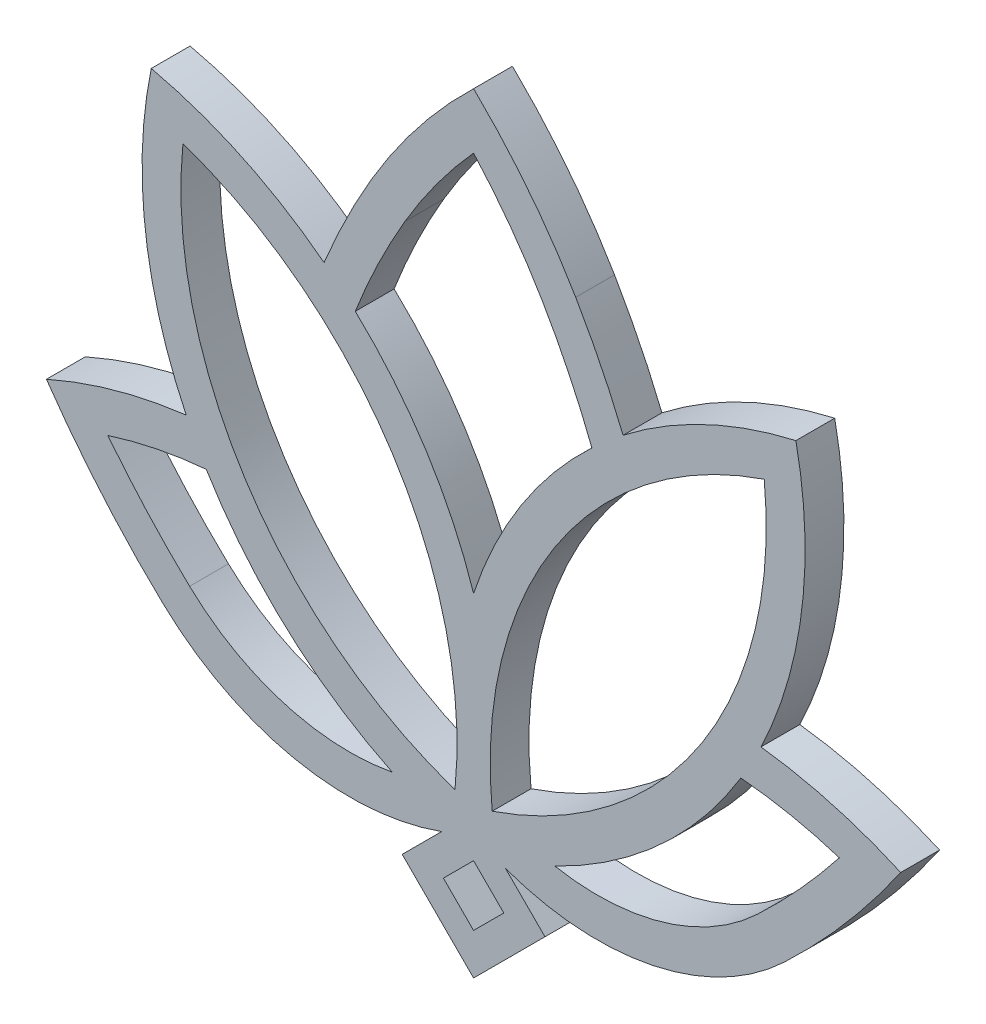
SolidWorks part; units mm, degrees
ref_plane "Front Plane" through (0, 0, 0) normal (0, 0, 1) x (1, 0, 0)
ref_plane "Top Plane" through (0, 0, 0) normal (0, 1, 0) x (1, 0, 0)
ref_plane "Right Plane" through (0, 0, 0) normal (1, 0, 0) x (0, 0, -1)
sketch "Sketch1" plane through (0, 0, 0) normal (0, 0, 1) x (1, 0, 0)
  line L0 (135.2147, 495.9847) -> (817.8814, 495.9847) construction
  line L1 (0, 30.9437) -> (0, -6.9458) construction
  line L2 (0, -55) -> (0, 55) construction
  line L3 (0, 0) -> (1.8385, 1.8385)
  line L4 (1.8385, 1.8385) -> (0.8237, 2.8533)
  line L5 (7.4845, 14.8656) -> (0.479, 3.9593) construction
  line L6 (-5, 0) -> (5, 0) construction
  line L7 (55, 0) -> (-55, 0) construction
  line L9 (0, 1.0607) -> (0.7778, 1.8385)
  line L10 (0.7778, 1.8385) -> (0, 2.6163)
  line L11 (-7.4845, 14.8656) -> (-0.479, 3.9593) construction
  line L12 (-0.7778, 1.8385) -> (0, 2.6163)
  line L13 (0, 1.0607) -> (-0.7778, 1.8385)
  line L14 (-1.8385, 1.8385) -> (-0.8237, 2.8533)
  line L15 (0, 0) -> (-1.8385, 1.8385)
  arc A0 (11, 7.8533) -> (7.4, 8.8533) centre (5.8871, -3.573) ccw
  arc A1 (0.8237, 2.8533) -> (8, 4.3533) centre (3.1917, 9.4406) ccw
  arc A2 (11, 7.8533) -> (8, 4.3533) centre (-7.1117, 20.3419) cw
  arc A3 (7.4, 8.8533) -> (8.3, 16.1351) centre (-2.8806, 13.8204) ccw
  arc A4 (8.3, 16.1351) -> (3.85, 14.0292) centre (10.8441, 5.0044) ccw
  arc A5 (3.85, 14.0292) -> (2.63, 16.4955) centre (-14.0152, 6.7268) ccw
  arc A6 (2.63, 16.4955) -> (0, 19.8333) centre (-10.8241, 8.5995) ccw
  arc A7 (1.7676, 15.9893) -> (3.0463, 13.3446) centre (-14.0152, 6.7268) cw
  arc A8 (1.7676, 15.9893) -> (0, 18.3974) centre (-10.8241, 8.5995) ccw
  arc A9 (3.0463, 13.3446) -> (0, 8.5778) centre (10.8441, 5.0044) ccw
  arc A10 (7.4845, 14.8656) -> (0.479, 3.9593) centre (10.8441, 5.0044) ccw
  arc A11 (7.4845, 14.8656) -> (0.479, 3.9593) centre (-2.8806, 13.8204) cw
  arc A12 (2.0916, 3.5423) -> (7.3131, 5.08) centre (3.1917, 9.4406) ccw
  arc A13 (9.4187, 7.3903) -> (7.3131, 5.08) centre (-7.1117, 20.3419) cw
  arc A14 (2.0916, 3.5423) -> (6.8833, 7.9019) centre (-2.8806, 13.8204) ccw
  arc A15 (6.8833, 7.9019) -> (9.4187, 7.3903) centre (5.8871, -3.573) cw
  arc A16 (-6.8833, 7.9019) -> (-9.4187, 7.3903) centre (-5.8871, -3.573) ccw
  arc A17 (-2.0916, 3.5423) -> (-6.8833, 7.9019) centre (2.8806, 13.8204) cw
  arc A18 (-9.4187, 7.3903) -> (-7.3131, 5.08) centre (7.1117, 20.3419) ccw
  arc A19 (-2.0916, 3.5423) -> (-7.3131, 5.08) centre (-3.1917, 9.4406) cw
  arc A20 (-7.4845, 14.8656) -> (-0.479, 3.9593) centre (2.8806, 13.8204) ccw
  arc A21 (-7.4845, 14.8656) -> (-0.479, 3.9593) centre (-10.8441, 5.0044) cw
  arc A22 (-3.0463, 13.3446) -> (0, 8.5778) centre (-10.8441, 5.0044) cw
  arc A23 (-1.7676, 15.9893) -> (0, 18.3974) centre (10.8241, 8.5995) cw
  arc A24 (-1.7676, 15.9893) -> (-3.0463, 13.3446) centre (14.0152, 6.7268) ccw
  arc A25 (-2.63, 16.4955) -> (0, 19.8333) centre (10.8241, 8.5995) cw
  arc A26 (-3.85, 14.0292) -> (-2.63, 16.4955) centre (14.0152, 6.7268) cw
  arc A27 (-8.3, 16.1351) -> (-3.85, 14.0292) centre (-10.8441, 5.0044) cw
  arc A28 (-7.4, 8.8533) -> (-8.3, 16.1351) centre (2.8806, 13.8204) cw
  arc A29 (-11, 7.8533) -> (-8, 4.3533) centre (7.1117, 20.3419) ccw
  arc A30 (-0.8237, 2.8533) -> (-8, 4.3533) centre (-3.1917, 9.4406) cw
  arc A31 (-11, 7.8533) -> (-7.4, 8.8533) centre (-5.8871, -3.573) cw
  point P40 (0, 0)
  point P75 (0, 0)
  point P76 (0, 0)
  point P77 (0, 0)
  dimension "D1" = 0
  dimension "D2" = 1
  dimension "D3" = 1
  dimension "D4" = 2.6
  dimension "D5" = 5
  dimension "D6" = 0
  dimension "D7" = 1
  dimension "D8" = 1
  dimension "D9" = 45
  dimension "D10" = 12.518
  dimension "D11" = 7
  dimension "D12" = 22
  dimension "D13" = 1
  dimension "D14" = 0.75
  dimension "D24" = 19.3
  dimension "D27" = 14.6
  dimension "D15" = 0.75
  dimension "D16" = 8
  dimension "D17" = 1.5
  dimension "D18" = 11
  dimension "D19" = 5
  dimension "D20" = 7.4
  dimension "D21" = 6
  dimension "D22" = 8.3
  dimension "D23" = 2.63
  dimension "D25" = 3.85
  dimension "D26" = 17
extrude "Boss-Extrude1" add sketch "Sketch1" along normal blind 1
